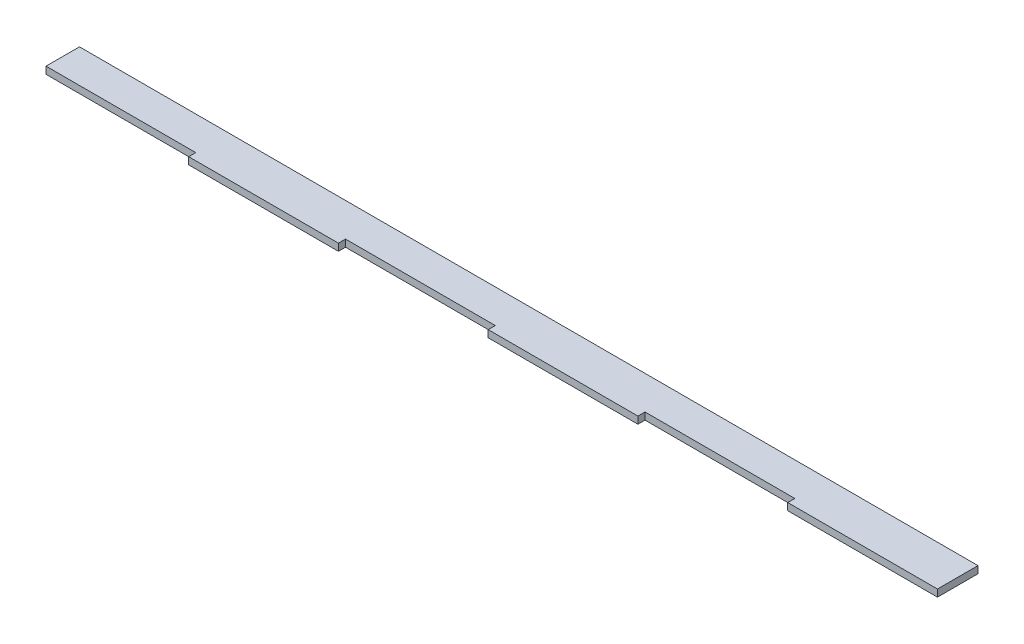
SolidWorks part; units mm, degrees
ref_plane "Front Plane" through (0, 0, 0) normal (0, 0, 1) x (1, 0, 0)
ref_plane "Top Plane" through (0, 0, 0) normal (0, 1, 0) x (1, 0, 0)
ref_plane "Right Plane" through (0, 0, 0) normal (1, 0, 0) x (0, 0, -1)
sketch "Sketch1" plane through (0, 0, 0) normal (0, 1, 0) x (1, 0, 0)
  line L0 (0, 0) -> (67.14, 0)
  line L1 (0, 0) -> (402.84, 0) construction
  line L2 (0, 0) -> (0, 15)
  line L3 (0, 15) -> (402.84, 15)
  line L4 (402.84, 0) -> (402.84, 15)
  line L5 (67.14, 0) -> (67.14, -3.175)
  line L6 (67.14, -3.175) -> (134.28, -3.175)
  line L7 (134.28, -3.175) -> (134.28, 0)
  line L8 (134.28, 0) -> (201.42, 0)
  line L9 (201.42, 0) -> (201.42, -3.175)
  line L10 (201.42, -3.175) -> (268.56, -3.175)
  line L11 (268.56, -3.175) -> (268.56, 0)
  line L12 (268.56, 0) -> (335.7, 0)
  line L13 (335.7, 0) -> (335.7, -3.175)
  line L14 (335.7, -3.175) -> (402.84, -3.175)
  line L15 (402.84, -3.175) -> (402.84, 0)
  dimension "D1" = 402.84
  dimension "D2" = 15
  dimension "D3" = 3.175
extrude "Boss-Extrude1" add sketch "Sketch1" along normal blind 3.175
